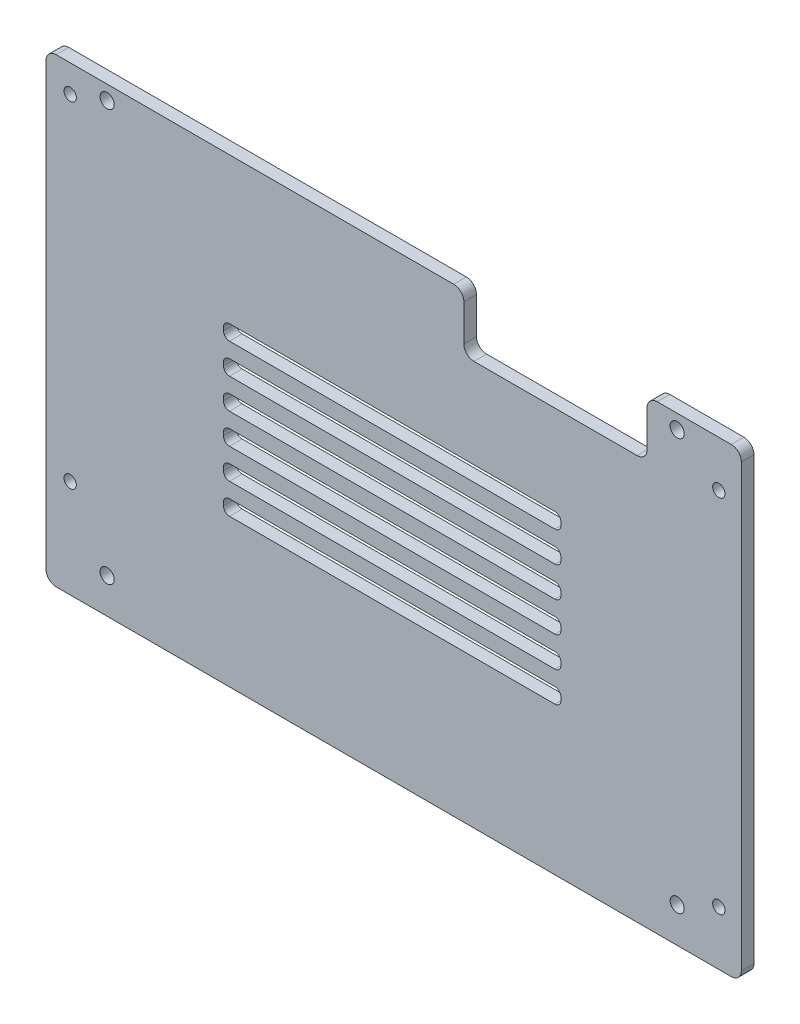
SolidWorks part; units mm, degrees
ref_plane "Front Plane" through (0, 0, 0) normal (0, 0, 1) x (1, 0, 0)
ref_plane "Top Plane" through (0, 0, 0) normal (0, 1, 0) x (1, 0, 0)
ref_plane "Right Plane" through (0, 0, 0) normal (1, 0, 0) x (0, 0, -1)
sketch "Sketch1" plane through (0, 0, 0) normal (0, 0, 1) x (1, 0, 0)
  line L0 (172.593, 116.2304) -> (2.921, 116.2304) construction
  line L1 (0.381, 116.2304) -> (105.391, 116.2304)
  line L2 (0.381, 116.2304) -> (0.381, 0.4064)
  line L3 (0.381, 0.4064) -> (175.133, 0.4064)
  line L4 (175.133, 116.2304) -> (175.133, 0.4064)
  line L5 (175.133, 113.6904) -> (175.133, 2.9464) construction
  line L6 (172.593, 0.4064) -> (2.921, 0.4064) construction
  line L7 (105.391, 116.2304) -> (105.391, 101.9855)
  line L8 (0.381, 113.6904) -> (0.381, 2.9464) construction
  line L13 (105.391, 101.9855) -> (151.4604, 101.9855)
  line L14 (151.4604, 101.9855) -> (151.4604, 116.2304)
  line L15 (151.4604, 116.2304) -> (175.133, 116.2304)
  line L22 (44.9659, 70.3213) -> (44.9659, 69.5593)
  line L23 (46.4899, 79.4653) -> (128.2621, 79.4653)
  line L25 (44.9659, 77.9413) -> (44.9659, 77.1793)
  line L26 (46.4899, 75.6553) -> (128.2621, 75.6553)
  line L27 (129.7861, 77.9413) -> (129.7861, 77.1793)
  line L28 (46.4899, 71.8453) -> (128.2621, 71.8453)
  line L29 (129.7861, 70.3213) -> (129.7861, 69.5593)
  line L30 (46.4899, 68.0353) -> (128.2621, 68.0353)
  line L31 (44.9659, 62.7013) -> (44.9659, 61.9393)
  line L32 (46.4899, 64.2253) -> (128.2621, 64.2253)
  line L33 (129.7861, 62.7013) -> (129.7861, 61.9393)
  line L34 (46.4899, 60.4153) -> (128.2621, 60.4153)
  line L35 (44.9659, 55.0813) -> (44.9659, 54.3193)
  line L36 (46.4899, 56.6053) -> (128.2621, 56.6053)
  line L37 (129.7861, 55.0813) -> (129.7861, 54.3193)
  line L38 (46.4899, 52.7953) -> (128.2621, 52.7953)
  line L39 (44.9659, 47.4613) -> (44.9659, 46.6993)
  line L40 (46.4899, 48.9853) -> (128.2621, 48.9853)
  line L41 (129.7861, 47.4613) -> (129.7861, 46.6993)
  line L42 (46.4899, 45.1753) -> (128.2621, 45.1753)
  line L43 (44.9659, 39.8413) -> (44.9659, 39.0793)
  line L44 (46.4899, 41.3653) -> (128.2621, 41.3653)
  line L45 (129.7861, 39.8413) -> (129.7861, 39.0793)
  line L46 (46.4899, 37.5553) -> (128.2621, 37.5553)
  circle A0 centre (6.4516, 109.3724) radius 1.5494
  circle A1 centre (169.4688, 104.6734) radius 1.5494
  circle A2 centre (169.4688, 14.0208) radius 1.5494
  circle A3 centre (6.4516, 25.0952) radius 1.5494
  circle A4 centre (15.748, 112.649) radius 1.778
  circle A5 centre (159.004, 112.649) radius 1.778
  circle A6 centre (15.748, 9.271) radius 1.778
  circle A7 centre (159.004, 9.271) radius 1.778
  arc A8 (129.7861, 77.1793) -> (128.2621, 75.6553) centre (128.2621, 77.1793) cw
  arc A9 (129.7861, 77.9413) -> (128.2621, 79.4653) centre (128.2621, 77.9413) ccw
  arc A10 (44.9659, 77.9413) -> (46.4899, 79.4653) centre (46.4899, 77.9413) cw
  arc A11 (44.9659, 77.1793) -> (46.4899, 75.6553) centre (46.4899, 77.1793) ccw
  arc A12 (129.7861, 39.0793) -> (128.2621, 37.5553) centre (128.2621, 39.0793) cw
  arc A13 (129.7861, 39.8413) -> (128.2621, 41.3653) centre (128.2621, 39.8413) ccw
  arc A14 (46.4899, 37.5553) -> (44.9659, 39.0793) centre (46.4899, 39.0793) cw
  arc A15 (44.9659, 39.8413) -> (46.4899, 41.3653) centre (46.4899, 39.8413) cw
  arc A16 (46.4899, 45.1753) -> (44.9659, 46.6993) centre (46.4899, 46.6993) cw
  arc A17 (46.4899, 48.9853) -> (44.9659, 47.4613) centre (46.4899, 47.4613) ccw
  arc A18 (129.7861, 46.6993) -> (128.2621, 45.1753) centre (128.2621, 46.6993) cw
  arc A19 (129.7861, 47.4613) -> (128.2621, 48.9853) centre (128.2621, 47.4613) ccw
  arc A20 (129.7861, 54.3193) -> (128.2621, 52.7953) centre (128.2621, 54.3193) cw
  arc A21 (129.7861, 55.0813) -> (128.2621, 56.6053) centre (128.2621, 55.0813) ccw
  arc A22 (44.9659, 54.3193) -> (46.4899, 52.7953) centre (46.4899, 54.3193) ccw
  arc A23 (44.9659, 55.0813) -> (46.4899, 56.6053) centre (46.4899, 55.0813) cw
  arc A24 (129.7861, 61.9393) -> (128.2621, 60.4153) centre (128.2621, 61.9393) cw
  arc A25 (129.7861, 62.7013) -> (128.2621, 64.2253) centre (128.2621, 62.7013) ccw
  arc A26 (129.7861, 70.3213) -> (128.2621, 71.8453) centre (128.2621, 70.3213) ccw
  arc A27 (46.4899, 60.4153) -> (44.9659, 61.9393) centre (46.4899, 61.9393) cw
  arc A28 (44.9659, 62.7013) -> (46.4899, 64.2253) centre (46.4899, 62.7013) cw
  arc A29 (44.9659, 70.3213) -> (46.4899, 71.8453) centre (46.4899, 70.3213) cw
  arc A30 (46.4899, 68.0353) -> (44.9659, 69.5593) centre (46.4899, 69.5593) cw
  arc A31 (129.7861, 69.5593) -> (128.2621, 68.0353) centre (128.2621, 69.5593) cw
  point P19 (0, 0)
  point P41 (87.376, 57.912)
  point P54 (87.376, 79.4653)
  point P81 (44.9659, 79.4653)
  point P84 (44.9659, 75.6553)
  dimension "D1" = 3.556
  dimension "D7" = 44.9659
  dimension "D3" = 3.0988
  dimension "D4" = 1.524
  dimension "D8" = 87.376
  dimension "D9" = 105.391
  dimension "D10" = 129.7861
  dimension "D11" = 151.4604
  dimension "D28" = 6
extrude "Boss-Extrude1" add sketch "Sketch1" along normal blind 3.175
fillet "Fillet2" radius 2.54 4 edges at (151.4604, 116.2304, 1.5875) (151.4604, 101.9855, 1.5875) (105.391, 116.2304, 1.5875) (105.391, 101.9855, 1.5875)
fillet "Fillet3" radius 2.54 4 edges at (175.133, 116.2304, 1.5875) (175.133, 0.4064, 1.5875) (0.381, 0.4064, 1.5875) (0.381, 116.2304, 1.5875)
